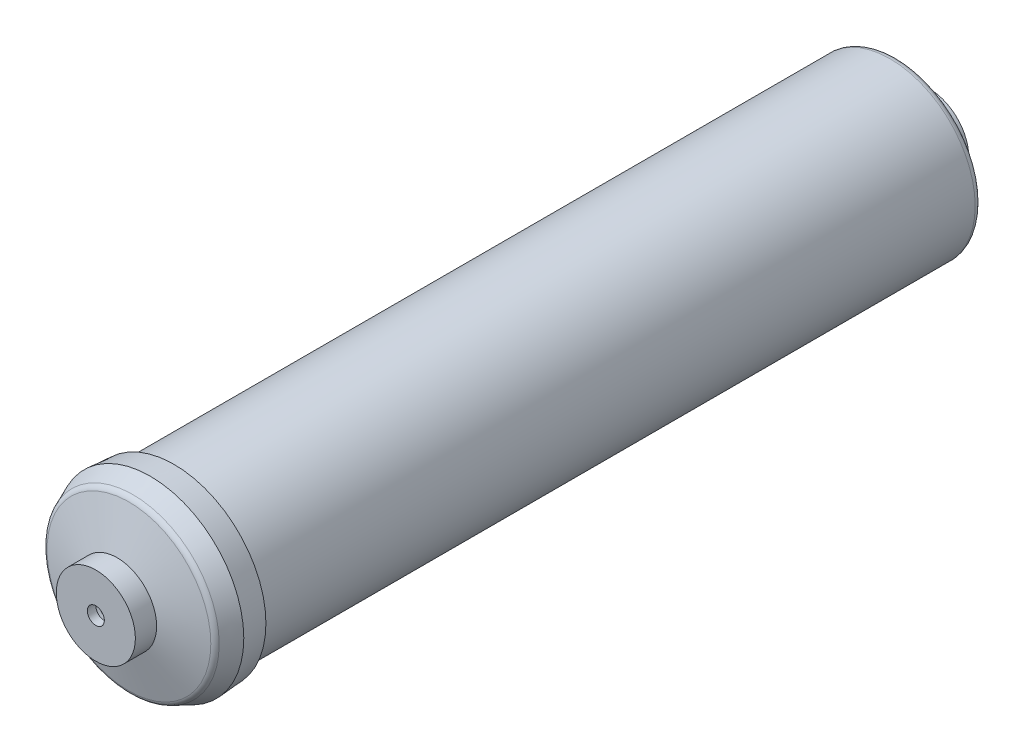
SolidWorks part; units mm, degrees
material "PC High Viscosity"
ref_plane "Front Plane" through (0, 0, 0) normal (0, 0, 1) x (1, 0, 0)
ref_plane "Top Plane" through (0, 0, 0) normal (0, 1, 0) x (1, 0, 0)
ref_plane "Right Plane" through (0, 0, 0) normal (1, 0, 0) x (0, 0, -1)
sketch "Sketch1" plane through (0, 0, 0) normal (1, 0, 0) x (0, 0, -1)
  line L0 (0, 0) -> (311.15, 0) construction
  line L1 (0, 0) -> (0, 14.7638) construction
  line L2 (0, 14.7638) -> (7.9375, 14.7638)
  line L3 (7.9375, 14.7638) -> (12.7, 31.75)
  line L4 (12.7, 31.75) -> (20.32, 34.925)
  line L5 (20.32, 34.925) -> (29.21, 34.29)
  line L6 (29.21, 34.29) -> (29.21, 31.75)
  line L7 (29.21, 31.75) -> (298.45, 31.75)
  line L8 (298.45, 31.75) -> (303.2125, 14.7637)
  line L9 (303.2125, 14.7637) -> (311.15, 14.7638)
  line L10 (311.15, 14.7638) -> (311.15, 0) construction
  line L11 (3.175, 11.5888) -> (10.3447, 11.5888)
  line L12 (10.3447, 11.5888) -> (15.3417, 29.4111)
  line L13 (15.3417, 29.4111) -> (20.8455, 31.7044)
  line L14 (20.8455, 31.7044) -> (26.035, 31.3337)
  line L15 (26.035, 31.3337) -> (26.035, 28.575)
  line L16 (26.035, 28.575) -> (296.0428, 28.575)
  line L17 (296.0428, 28.575) -> (300.8053, 11.5888)
  line L18 (300.8053, 11.5888) -> (307.975, 11.5888)
  line L19 (300.8053, 11.5888) -> (311.15, 11.5888) construction
  line L20 (307.975, 11.5888) -> (307.975, 3.175)
  line L21 (307.975, 3.175) -> (311.15, 3.175)
  line L22 (311.15, 3.175) -> (311.15, 14.7638)
  line L23 (0, 11.5888) -> (10.3447, 11.5888) construction
  line L24 (0, 14.7638) -> (0, 3.175)
  line L25 (0, 3.175) -> (3.175, 3.175)
  line L26 (3.175, 3.175) -> (3.175, 11.5888)
  dimension "D1" = 311.15
  dimension "D2" = 7.9375
  dimension "D3" = 29.5275
  dimension "D4" = 63.5
  dimension "D5" = 12.7
  dimension "D6" = 69.85
  dimension "D7" = 7.62
  dimension "D8" = 63.5
  dimension "D9" = 8.89
  dimension "D10" = 2.54
  dimension "D12" = 3.175
  dimension "D13" = 6.35
  dimension "D11" = 3.175
revolve "Revolve1" add sketch "Sketch1" angle 360 about L0
fillet "Fillet1" radius 2.54 2 edges at (31.75, 0, -12.7) (31.75, 0, -298.45)
